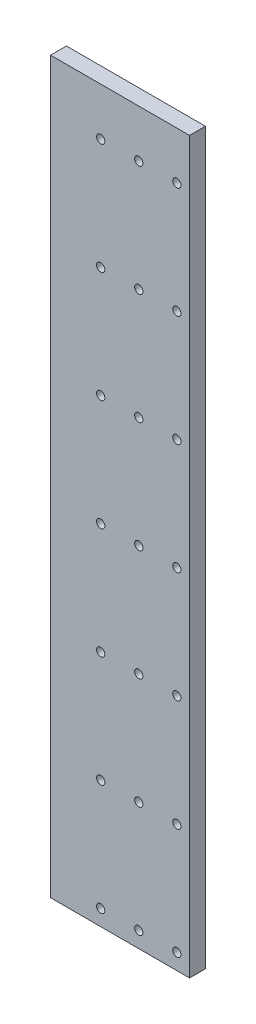
SolidWorks part; units mm, degrees
ref_plane "Plan de face" through (0, 0, 0) normal (0, 0, 1) x (1, 0, 0)
ref_plane "Plan de dessus" through (0, 0, 0) normal (0, 1, 0) x (1, 0, 0)
ref_plane "Plan de droite" through (0, 0, 0) normal (1, 0, 0) x (0, 0, -1)
sketch "Main" plane through (0, 0, 0) normal (0, 0, 1) x (1, 0, 0)
  line L1 (24.8105, 240) -> (68.6105, 240)
  line L2 (24.8105, 240) -> (24.8105, 10)
  line L3 (24.8105, 10) -> (68.6105, 10)
  line L4 (68.6105, 240) -> (68.6105, 10)
  dimension "D1" = 230
  dimension "D2" = 43.8
extrude "Main Extrusion" add sketch "Main" along normal blind 2.5
sketch "Main Fix Sketch" plane through (0, 0, 0) normal (0, 0, -1) x (-1, 0, 0)
  line L0 (-68.6105, 240) -> (-24.8105, 240) construction
  line L1 (-60.6105, 240) -> (-68.6105, 240)
  line L2 (-60.6105, 240) -> (-60.6105, 10)
  line L3 (-60.6105, 10) -> (-68.6105, 10)
  line L4 (-68.6105, 240) -> (-68.6105, 10)
  line L5 (-24.8105, 10) -> (-68.6105, 10) construction
  line L6 (-68.6105, 10) -> (-68.6105, 240) construction
  line L7 (-68.6105, 10) -> (-68.6105, 240) construction
  dimension "D1" = 0
  dimension "D2" = 8
extrude "Main Fix - Extrusion" add sketch "Main Fix Sketch" along normal blind 2.5
sketch "Main Fix Hole Sketch" plane through (0, 0, 2.5) normal (0, 0, 1) x (1, 0, 0)
  line L0 (68.6105, 10) -> (68.6105, 240) construction
  line L1 (68.6105, 240) -> (24.8105, 240) construction
  circle A0 centre (64.6105, 225) radius 1.3
  dimension "D1" = 2.6
  dimension "D2" = 4
  dimension "D3" = 15
extrude "Main Fix Hole" cut sketch "Main Fix Hole Sketch" against normal through all
pattern_linear "Main Fix Hole Horizontal Repeat" count 3 spacing 12 along (-1, 0, 0) of "Main Fix Hole"
pattern_linear "Fix Hole Vertical Repeat" count 7 spacing 35 along (0, -1, 0) of "Main Fix Hole", "Main Fix Hole Horizontal Repeat"
sketch "Vertical Rainure" plane through (0, 0, 0) normal (0, 0, -1) x (-1, 0, 0)
  line L0 (-24.8105, 240) -> (-24.8105, 10) construction
  line L1 (-24.8105, 10) -> (-29.8105, 10)
  line L2 (-24.8105, 10) -> (-24.8105, 240)
  line L3 (-24.8105, 240) -> (-29.8105, 240)
  line L4 (-29.8105, 10) -> (-29.8105, 240)
  dimension "D1" = 5
extrude "Vertical Rainure - Extrusion" add sketch "Vertical Rainure" along normal blind 2.5
sketch "Horizontal Rainure" plane through (0, 0, 0) normal (0, 0, -1) x (-1, 0, 0)
  line L0 (-68.6105, 10) -> (-60.6105, 10) construction
  line L1 (-60.6105, 16) -> (-29.8105, 16)
  line L2 (-60.6105, 16) -> (-60.6105, 10)
  line L3 (-60.6105, 10) -> (-29.8105, 10)
  line L4 (-29.8105, 16) -> (-29.8105, 10)
  dimension "D1" = 6
extrude "Horizontal Rainure - Extrusion" add sketch "Horizontal Rainure" along normal blind 2.5
pattern_linear "Répétition linéaire1" count 8 spacing 32 along (0, 1, 0) of "Horizontal Rainure - Extrusion"
pattern_linear "Répétition linéaire2" count 2 spacing 18 along (1, 0, 0) of "Vertical Rainure - Extrusion"
sketch "Slot Sketch" plane through (0, 176, 0) normal (0, 1, 0) x (1, 0, 0)
  line L0 (24.8105, 15) -> (29.8105, 15)
  line L1 (29.8105, 0) -> (42.8105, 0) construction
  line L2 (24.8105, 15) -> (24.8105, 10)
  line L3 (24.8105, 10) -> (22.6105, 10)
  line L4 (22.6105, 10) -> (22.6105, 13)
  line L5 (22.6105, 13) -> (18.8105, 10)
  line L6 (18.8105, 10) -> (18.8105, 5)
  line L7 (18.8105, 5) -> (22.6105, 2)
  line L8 (22.6105, 2) -> (22.6105, 5)
  line L9 (22.6105, 5) -> (24.8105, 5)
  line L10 (24.8105, 5) -> (24.8105, 0)
  line L11 (24.8105, 0) -> (36.3105, 0)
  line L12 (24.8105, -2.5) -> (24.8105, 2.5) construction
  line L13 (29.8105, 15) -> (36.3105, 0)
  line L15 (68.6105, -2.5) -> (24.8105, -2.5) construction
  dimension "D1" = 5
  dimension "D2" = 8
  dimension "D3" = 2.2
  dimension "D4" = 3.8
  dimension "D5" = 5
  dimension "D6" = 7.5
  dimension "D7" = 17.5
extrude "Slot Sketch Extrusion" add sketch "Slot Sketch" along normal blind 40
ref_plane "Plan1" through (32.8105, 0, 0) normal (-1, 0, 0) x (0, 0, 1)
ref_axis "Axe Fox Clip Fix Sketch" through (32.8105, 252, -15) along (0, -1, 0)
sketch "Clip Fix Sketch" plane through (0, 0, -15) normal (0, 0, -1) x (-1, 0, 0)
  line L0 (-24.8105, 216) -> (-24.8105, 176) construction
  line L1 (-26.8105, 178) -> (-28.8105, 178)
  line L2 (-26.8105, 178) -> (-26.8105, 182)
  line L3 (-26.8105, 182) -> (-28.8105, 182)
  line L4 (-28.8105, 178) -> (-28.8105, 182)
  line L5 (-29.8105, 176) -> (-24.8105, 176) construction
  line L7 (-28.8105, 210) -> (-26.8105, 210)
  line L8 (-28.8105, 210) -> (-28.8105, 214)
  line L9 (-28.8105, 214) -> (-26.8105, 214)
  line L10 (-26.8105, 210) -> (-26.8105, 214)
  line L11 (-29.8105, 216) -> (-24.8105, 216) construction
  line L12 (-26.8105, 205) -> (-28.8105, 205)
  line L13 (-26.8105, 205) -> (-26.8105, 201)
  line L14 (-26.8105, 201) -> (-28.8105, 201)
  line L15 (-28.8105, 205) -> (-28.8105, 201)
  line L16 (-28.8105, 191) -> (-26.8105, 191)
  line L17 (-28.8105, 191) -> (-28.8105, 187)
  line L18 (-28.8105, 187) -> (-26.8105, 187)
  line L19 (-26.8105, 191) -> (-26.8105, 187)
  dimension "D1" = 4
  dimension "D2" = 2
  dimension "D3" = 2
  dimension "D4" = 2
  dimension "D5" = 2
  dimension "D6" = 5
  dimension "D7" = 5
revolve "Clip Fix Extrusion" cut sketch "Clip Fix Sketch" angle 360 about axis through (32.8105, 252, -15) along (0, -1, 0)
sketch "Slot Hole Sketch" plane through (18.8105, 0, 0) normal (-1, 0, 0) x (0, 0, 1)
  line L0 (-10, 176) -> (-5, 176) construction
  line L1 (-5, 216) -> (-5, 176) construction
  circle A0 centre (-7.5, 196) radius 1.3
  point P5 (-7.5, 176)
  point P8 (-5, 196)
  dimension "D1" = 2.6
extrude "Slot Hole Extrusion" cut sketch "Slot Hole Sketch" against normal through all
sketch "Slot Hole Head" plane through (32.8105, 0, 0) normal (-1, 0, 0) x (0, 0, 1)
  circle A0 centre (-7.5, 196) radius 3
  circle A1 centre (-7.5, 196) radius 1.3 construction
  dimension "D1" = 6
extrude "Slot Hole Head Extrusion" cut sketch "Slot Hole Head" along normal mid plane 6
pattern_linear "Répétition linéaire3" count 3 spacing 80 along (0, -1, 0) of "Slot Sketch Extrusion", "Clip Fix Extrusion", "Slot Hole Extrusion", "Slot Hole Head Extrusion"
